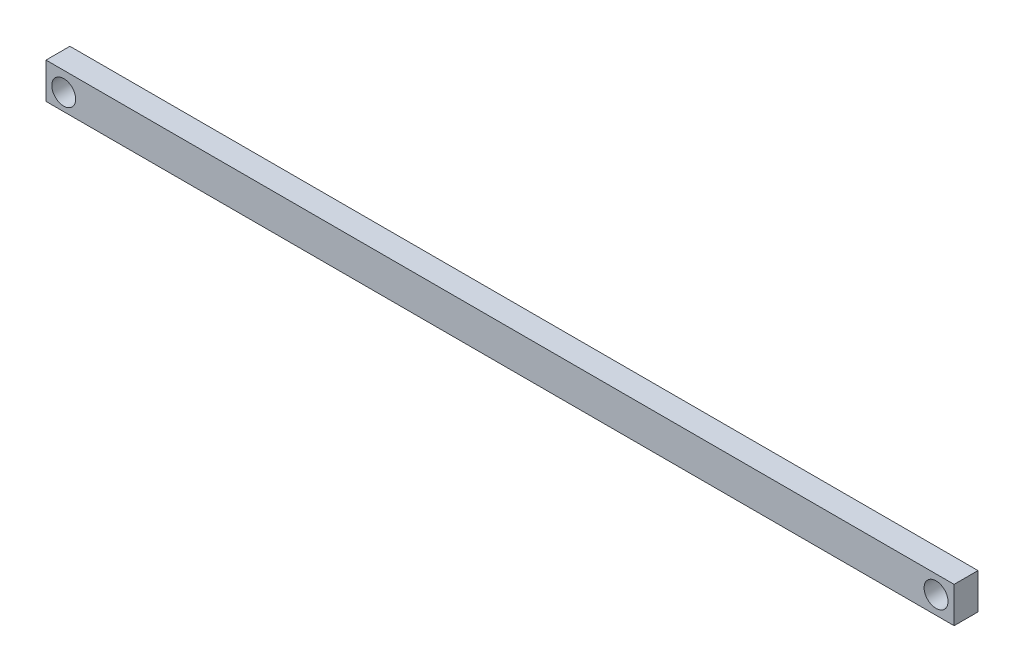
SolidWorks part; units mm, degrees
ref_plane "前视基准面" through (0, 0, 0) normal (0, 0, 1) x (1, 0, 0)
ref_plane "上视基准面" through (0, 0, 0) normal (0, 1, 0) x (1, 0, 0)
ref_plane "右视基准面" through (0, 0, 0) normal (1, 0, 0) x (0, 0, -1)
sketch "草图1" plane through (0, 0, 0) normal (0, 0, 1) x (1, 0, 0)
  line L1 (-83.6232, 22.9433) -> (296.3768, 22.9433)
  line L2 (-83.6232, 22.9433) -> (-83.6232, 7.9433)
  line L3 (-83.6232, 7.9433) -> (296.3768, 7.9433)
  line L4 (296.3768, 22.9433) -> (296.3768, 7.9433)
extrude "凸台-拉伸1" add sketch "草图1" along normal blind 10
sketch "草图2" plane through (0, 0, 10) normal (0, 0, 1) x (1, 0, 0)
  circle A0 centre (-76.1992, 14.9573) radius 5
  circle A1 centre (288.8242, 15.4433) radius 5
  point P4 (288.8242, 15.4433)
extrude "切除-拉伸1" cut sketch "草图2" against normal through all
